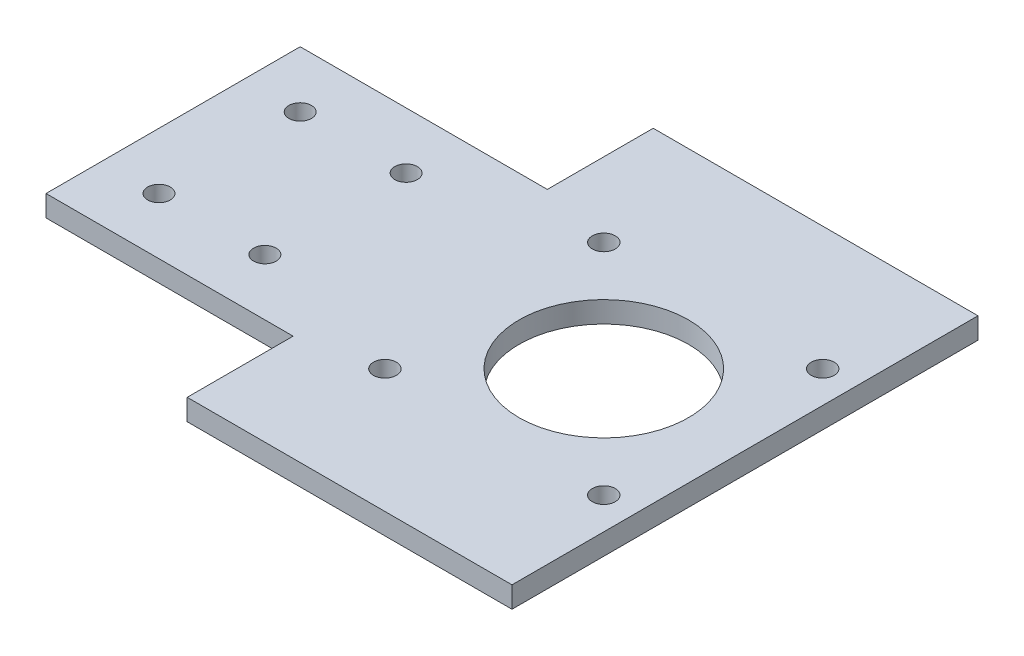
SolidWorks part; units mm, degrees
ref_plane "前视基准面" through (0, 0, 0) normal (0, 0, 1) x (1, 0, 0)
ref_plane "上视基准面" through (0, 0, 0) normal (0, 1, 0) x (1, 0, 0)
ref_plane "右视基准面" through (0, 0, 0) normal (1, 0, 0) x (0, 0, -1)
other "Configuration Table"
sketch "草图1" plane through (0, 0, 0) normal (0, 1, 0) x (1, 0, 0)
  line L0 (0, 0) -> (0, 36)
  line L1 (0, 36) -> (35, 36)
  line L2 (35, 36) -> (35, 51)
  line L3 (35, 51) -> (81, 51)
  line L4 (81, 51) -> (81, -15)
  line L5 (81, -15) -> (35, -15)
  line L6 (35, -15) -> (35, 0)
  line L7 (35, 0) -> (0, 0)
  dimension "D1" = 36
  dimension "D2" = 35
  dimension "D3" = 46
  dimension "D4" = 66
extrude "凸台-拉伸1" add sketch "草图1" along normal blind 3
sketch "草图2" plane through (0, 3, 0) normal (0, 1, 0) x (1, 0, 0)
  line L0 (35, 36) -> (0, 36) construction
  line L1 (8, 28) -> (23, 28) construction
  line L2 (8, 28) -> (8, 8) construction
  line L3 (8, 8) -> (23, 8) construction
  line L4 (23, 28) -> (23, 8) construction
  line L5 (0, 36) -> (0, 0) construction
  line L6 (81, -15) -> (81, 51) construction
  line L7 (81, 18) -> (0, 18) construction
  circle A0 centre (8, 28) radius 1.6
  circle A1 centre (23, 28) radius 1.6
  circle A2 centre (8, 8) radius 1.6
  circle A3 centre (23, 8) radius 1.6
  circle A4 centre (61, 18) radius 12
  dimension "D5" = 3.2
  dimension "D6" = 24
  dimension "D1" = 20
  dimension "D2" = 8
  dimension "D3" = 8
  dimension "D4" = 15
  dimension "D7" = 20
extrude "切除-拉伸1" cut sketch "草图2" against normal blind 3
sketch "草图4" plane through (0, 0, 0) normal (0, -1, 0) x (1, 0, 0)
  circle A1 centre (45.5, -33.5) radius 1.625
  circle A2 centre (45.5, -33.5) radius 1.625
  circle A3 centre (76.5, -33.5) radius 1.625
  circle A4 centre (76.5, -33.5) radius 1.625
  circle A5 centre (76.5, -2.5) radius 1.625
  circle A6 centre (76.5, -2.5) radius 1.625
  circle A7 centre (45.5, -2.5) radius 1.625
  circle A8 centre (45.5, -2.5) radius 1.625
  dimension "D1" = 0
  dimension "D2" = 0
  dimension "D3" = 0
  dimension "D4" = 0
extrude "切除-拉伸2" cut sketch "草图4" against normal through all
